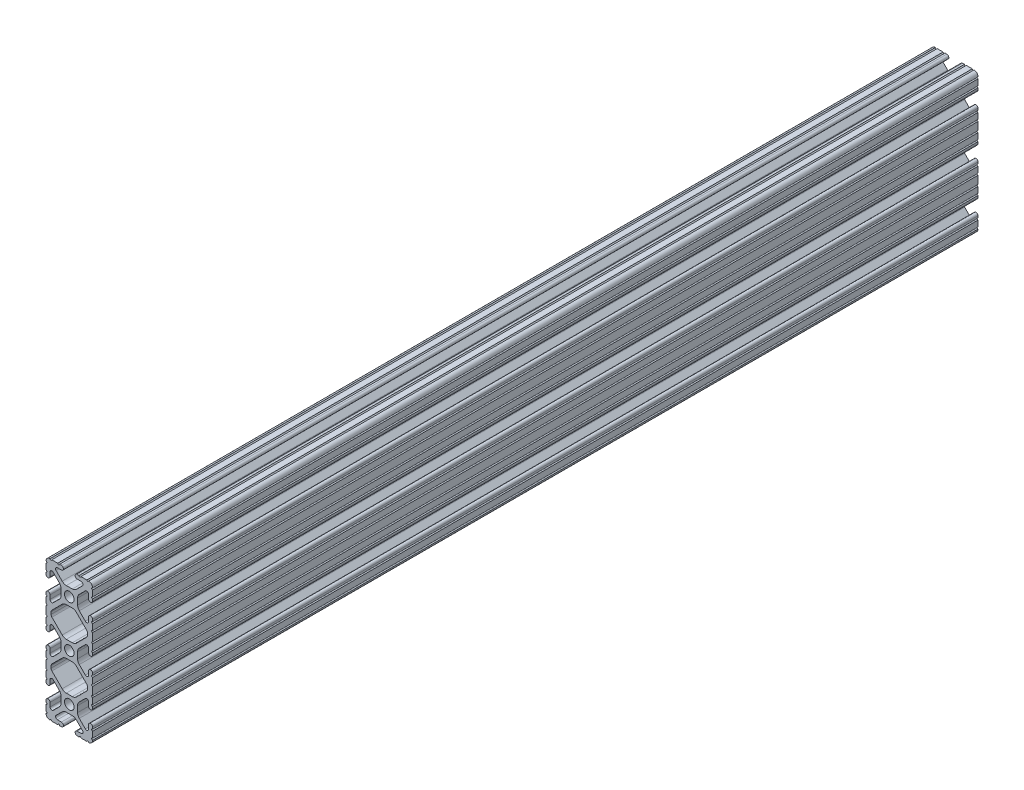
SolidWorks part; units mm, degrees
ref_plane "Front" through (0, 0, 0) normal (0, 0, 1) x (1, 0, 0)
ref_plane "Top" through (0, 0, 0) normal (0, 1, 0) x (1, 0, 0)
ref_plane "Right" through (0, 0, 0) normal (1, 0, 0) x (0, 0, -1)
sketch "Sketch1" plane through (0, 0, 0) normal (0, 0, 1) x (1, 0, 0)
  line L0 (-7.4908, -34.8742) -> (7.4908, -34.8742) construction
  line L1 (-3.1974, -36.9951) -> (3.1974, -36.9951) construction
  line L2 (-7.4908, 34.8742) -> (7.4908, 34.8742) construction
  line L3 (-3.1974, 36.9951) -> (3.1974, 36.9951) construction
  line L16 (-9.9314, -12.1463) -> (-9.9314, -13.2537)
  line L17 (-3.8759, -5.4384) -> (-9.4702, -11.0327)
  line L18 (1.6308, -4.5085) -> (-1.6308, -4.5085)
  line L19 (9.4702, -11.0327) -> (3.8759, -5.4384)
  line L20 (9.9314, -13.2537) -> (9.9314, -12.1463)
  line L21 (3.8759, -19.9616) -> (9.4702, -14.3673)
  line L22 (-1.6308, -20.8915) -> (1.6308, -20.8915)
  line L23 (-9.4702, -14.3673) -> (-3.8759, -19.9616)
  line L32 (-9.9314, 13.2537) -> (-9.9314, 12.1463)
  line L33 (-3.8759, 19.9616) -> (-9.4702, 14.3673)
  line L34 (1.6308, 20.8915) -> (-1.6308, 20.8915)
  line L35 (9.4702, 14.3673) -> (3.8759, 19.9616)
  line L36 (9.9314, 12.1463) -> (9.9314, 13.2537)
  line L37 (3.8759, 5.4384) -> (9.4702, 11.0327)
  line L38 (-1.6308, 4.5085) -> (1.6308, 4.5085)
  line L39 (-9.4702, 11.0327) -> (-3.8759, 5.4384)
  line L152 (-12.7, 34.9504) -> (-12.7, 31.7246)
  line L153 (-12.7, 30.7086) -> (-12.7, 29.7023)
  line L154 (-10.4902, 29.7023) -> (-10.4902, 31.8748)
  line L155 (-8.7558, 32.5932) -> (-5.4384, 29.2759)
  line L156 (-4.5085, 27.0308) -> (-4.5085, 23.7692)
  line L157 (-5.4384, 21.5241) -> (-8.7558, 18.2068)
  line L158 (-10.4902, 18.9252) -> (-10.4902, 21.0977)
  line L159 (-12.7, 21.0977) -> (-12.7, 20.0914)
  line L160 (-12.7, 19.0754) -> (-12.7, 15.8496)
  line L161 (-12.7, 14.8336) -> (-12.7, 10.5664)
  line L162 (-12.7, 9.5504) -> (-12.7, 6.3246)
  line L163 (-12.7, 5.3086) -> (-12.7, 4.3023)
  line L164 (-10.4902, 4.3023) -> (-10.4902, 6.4748)
  line L165 (-8.7558, 7.1932) -> (-5.4384, 3.8759)
  line L166 (-4.5085, 1.6308) -> (-4.5085, -1.6308)
  line L167 (-5.4384, -3.8759) -> (-8.7558, -7.1932)
  line L168 (-10.4902, -6.4748) -> (-10.4902, -4.3023)
  line L169 (-12.7, -4.3023) -> (-12.7, -5.3086)
  line L170 (-12.7, -6.3246) -> (-12.7, -9.5504)
  line L171 (-12.7, -10.5664) -> (-12.7, -14.8336)
  line L172 (-12.7, -15.8496) -> (-12.7, -19.0754)
  line L173 (-12.7, -20.0914) -> (-12.7, -21.0977)
  line L174 (-10.4902, -21.0977) -> (-10.4902, -18.9252)
  line L175 (-8.7558, -18.2068) -> (-5.4384, -21.5241)
  line L176 (-4.5085, -23.7692) -> (-4.5085, -27.0308)
  line L177 (-5.4384, -29.2759) -> (-8.7558, -32.5932)
  line L178 (-10.4902, -31.8748) -> (-10.4902, -29.7023)
  line L179 (-12.7, -29.7023) -> (-12.7, -30.7086)
  line L180 (-12.7, -31.7246) -> (-12.7, -34.9504)
  line L181 (-9.5504, -38.1) -> (-6.3246, -38.1)
  line L182 (-5.3086, -38.1) -> (-4.3023, -38.1)
  line L183 (-4.3023, -35.8902) -> (-6.4748, -35.8902)
  line L184 (-7.1932, -34.1558) -> (-3.8759, -30.8384)
  line L185 (-1.6308, -29.9085) -> (1.6308, -29.9085)
  line L186 (3.8759, -30.8384) -> (7.1932, -34.1558)
  line L187 (6.4748, -35.8902) -> (4.3023, -35.8902)
  line L188 (4.3023, -38.1) -> (5.3086, -38.1)
  line L189 (6.3246, -38.1) -> (9.5504, -38.1)
  line L190 (12.7, -34.9504) -> (12.7, -31.7246)
  line L191 (12.7, -30.7086) -> (12.7, -29.7023)
  line L192 (10.4902, -29.7023) -> (10.4902, -31.8748)
  line L193 (8.7558, -32.5932) -> (5.4384, -29.2759)
  line L194 (4.5085, -27.0308) -> (4.5085, -23.7692)
  line L195 (5.4384, -21.5241) -> (8.7558, -18.2068)
  line L196 (10.4902, -18.9252) -> (10.4902, -21.0977)
  line L197 (12.7, -21.0977) -> (12.7, -20.0914)
  line L198 (12.7, -19.0754) -> (12.7, -15.8496)
  line L199 (12.7, -14.8336) -> (12.7, -10.5664)
  line L200 (12.7, -9.5504) -> (12.7, -6.3246)
  line L201 (12.7, -5.3086) -> (12.7, -4.3023)
  line L202 (10.4902, -4.3023) -> (10.4902, -6.4748)
  line L203 (8.7558, -7.1932) -> (5.4384, -3.8759)
  line L204 (4.5085, -1.6308) -> (4.5085, 1.6308)
  line L205 (5.4384, 3.8759) -> (8.7558, 7.1932)
  line L206 (10.4902, 6.4748) -> (10.4902, 4.3023)
  line L207 (12.7, 4.3023) -> (12.7, 5.3086)
  line L208 (12.7, 6.3246) -> (12.7, 9.5504)
  line L209 (12.7, 10.5664) -> (12.7, 14.8336)
  line L210 (12.7, 15.8496) -> (12.7, 19.0754)
  line L211 (12.7, 20.0914) -> (12.7, 21.0977)
  line L212 (10.4902, 21.0977) -> (10.4902, 18.9252)
  line L213 (8.7558, 18.2068) -> (5.4384, 21.5241)
  line L214 (4.5085, 23.7692) -> (4.5085, 27.0308)
  line L215 (5.4384, 29.2759) -> (8.7558, 32.5932)
  line L216 (10.4902, 31.8748) -> (10.4902, 29.7023)
  line L217 (12.7, 29.7023) -> (12.7, 30.7086)
  line L218 (12.7, 31.7246) -> (12.7, 34.9504)
  line L219 (9.5504, 38.1) -> (6.3246, 38.1)
  line L220 (5.3086, 38.1) -> (4.3023, 38.1)
  line L221 (4.3023, 35.8902) -> (6.4748, 35.8902)
  line L222 (7.1932, 34.1558) -> (3.8759, 30.8384)
  line L223 (1.6308, 29.9085) -> (-1.6308, 29.9085)
  line L224 (-3.8759, 30.8384) -> (-7.1932, 34.1558)
  line L225 (-6.4748, 35.8902) -> (-4.3023, 35.8902)
  line L226 (-4.3023, 38.1) -> (-5.3086, 38.1)
  line L227 (-6.3246, 38.1) -> (-9.5504, 38.1)
  circle A2 centre (0, -25.4) radius 2.6035
  circle A4 centre (0, 0) radius 2.6035
  circle A6 centre (0, 25.4) radius 2.6035
  arc A18 (-9.9314, -13.2537) -> (-9.4702, -14.3673) centre (-8.3566, -13.2537) ccw
  arc A19 (-9.4702, -11.0327) -> (-9.9314, -12.1463) centre (-8.3566, -12.1463) ccw
  arc A20 (-1.6308, -4.5085) -> (-3.8759, -5.4384) centre (-1.6308, -7.6835) ccw
  arc A21 (3.8759, -5.4384) -> (1.6308, -4.5085) centre (1.6308, -7.6835) ccw
  arc A22 (9.9314, -12.1463) -> (9.4702, -11.0327) centre (8.3566, -12.1463) ccw
  arc A23 (9.4702, -14.3673) -> (9.9314, -13.2537) centre (8.3566, -13.2537) ccw
  arc A24 (1.6308, -20.8915) -> (3.8759, -19.9616) centre (1.6308, -17.7165) ccw
  arc A25 (-3.8759, -19.9616) -> (-1.6308, -20.8915) centre (-1.6308, -17.7165) ccw
  arc A36 (-9.9314, 12.1463) -> (-9.4702, 11.0327) centre (-8.3566, 12.1463) ccw
  arc A37 (-9.4702, 14.3673) -> (-9.9314, 13.2537) centre (-8.3566, 13.2537) ccw
  arc A38 (-1.6308, 20.8915) -> (-3.8759, 19.9616) centre (-1.6308, 17.7165) ccw
  arc A39 (3.8759, 19.9616) -> (1.6308, 20.8915) centre (1.6308, 17.7165) ccw
  arc A40 (9.9314, 13.2537) -> (9.4702, 14.3673) centre (8.3566, 13.2537) ccw
  arc A41 (9.4702, 11.0327) -> (9.9314, 12.1463) centre (8.3566, 12.1463) ccw
  arc A42 (1.6308, 4.5085) -> (3.8759, 5.4384) centre (1.6308, 7.6835) ccw
  arc A43 (-3.8759, 5.4384) -> (-1.6308, 4.5085) centre (-1.6308, 7.6835) ccw
  arc A168 (-10.5664, 38.1) -> (-12.7, 35.9664) centre (-10.592, 35.992) ccw
  arc A169 (-12.7, 34.9504) -> (-12.7, 35.9664) centre (-12.7, 35.4584) ccw
  arc A170 (-12.7, 30.7086) -> (-12.7, 31.7246) centre (-12.7, 31.2166) ccw
  arc A171 (-12.7, 29.7023) -> (-10.4902, 29.7023) centre (-11.5951, 29.7023) ccw
  arc A172 (-8.7558, 32.5932) -> (-10.4902, 31.8748) centre (-9.4742, 31.8748) ccw
  arc A173 (-4.5085, 27.0308) -> (-5.4384, 29.2759) centre (-7.6835, 27.0308) ccw
  arc A174 (-5.4384, 21.5241) -> (-4.5085, 23.7692) centre (-7.6835, 23.7692) ccw
  arc A175 (-10.4902, 18.9252) -> (-8.7558, 18.2068) centre (-9.4742, 18.9252) ccw
  arc A176 (-10.4902, 21.0977) -> (-12.7, 21.0977) centre (-11.5951, 21.0977) ccw
  arc A177 (-12.7, 19.0754) -> (-12.7, 20.0914) centre (-12.7, 19.5834) ccw
  arc A178 (-12.7, 14.8336) -> (-12.7, 15.8496) centre (-12.7, 15.3416) ccw
  arc A179 (-12.7, 9.5504) -> (-12.7, 10.5664) centre (-12.7, 10.0584) ccw
  arc A180 (-12.7, 5.3086) -> (-12.7, 6.3246) centre (-12.7, 5.8166) ccw
  arc A181 (-12.7, 4.3023) -> (-10.4902, 4.3023) centre (-11.5951, 4.3023) ccw
  arc A182 (-8.7558, 7.1932) -> (-10.4902, 6.4748) centre (-9.4742, 6.4748) ccw
  arc A183 (-4.5085, 1.6308) -> (-5.4384, 3.8759) centre (-7.6835, 1.6308) ccw
  arc A184 (-5.4384, -3.8759) -> (-4.5085, -1.6308) centre (-7.6835, -1.6308) ccw
  arc A185 (-10.4902, -6.4748) -> (-8.7558, -7.1932) centre (-9.4742, -6.4748) ccw
  arc A186 (-10.4902, -4.3023) -> (-12.7, -4.3023) centre (-11.5951, -4.3023) ccw
  arc A187 (-12.7, -6.3246) -> (-12.7, -5.3086) centre (-12.7, -5.8166) ccw
  arc A188 (-12.7, -10.5664) -> (-12.7, -9.5504) centre (-12.7, -10.0584) ccw
  arc A189 (-12.7, -15.8496) -> (-12.7, -14.8336) centre (-12.7, -15.3416) ccw
  arc A190 (-12.7, -20.0914) -> (-12.7, -19.0754) centre (-12.7, -19.5834) ccw
  arc A191 (-12.7, -21.0977) -> (-10.4902, -21.0977) centre (-11.5951, -21.0977) ccw
  arc A192 (-8.7558, -18.2068) -> (-10.4902, -18.9252) centre (-9.4742, -18.9252) ccw
  arc A193 (-4.5085, -23.7692) -> (-5.4384, -21.5241) centre (-7.6835, -23.7692) ccw
  arc A194 (-5.4384, -29.2759) -> (-4.5085, -27.0308) centre (-7.6835, -27.0308) ccw
  arc A195 (-10.4902, -31.8748) -> (-8.7558, -32.5932) centre (-9.4742, -31.8748) ccw
  arc A196 (-10.4902, -29.7023) -> (-12.7, -29.7023) centre (-11.5951, -29.7023) ccw
  arc A197 (-12.7, -31.7246) -> (-12.7, -30.7086) centre (-12.7, -31.2166) ccw
  arc A198 (-12.7, -35.9664) -> (-12.7, -34.9504) centre (-12.7, -35.4584) ccw
  arc A199 (-12.7, -35.9664) -> (-10.5664, -38.1) centre (-10.592, -35.992) ccw
  arc A200 (-9.5504, -38.1) -> (-10.5664, -38.1) centre (-10.0584, -38.1) ccw
  arc A201 (-5.3086, -38.1) -> (-6.3246, -38.1) centre (-5.8166, -38.1) ccw
  arc A202 (-4.3023, -38.1) -> (-4.3023, -35.8902) centre (-4.3023, -36.9951) ccw
  arc A203 (-7.1932, -34.1558) -> (-6.4748, -35.8902) centre (-6.4748, -34.8742) ccw
  arc A204 (-1.6308, -29.9085) -> (-3.8759, -30.8384) centre (-1.6308, -33.0835) ccw
  arc A205 (3.8759, -30.8384) -> (1.6308, -29.9085) centre (1.6308, -33.0835) ccw
  arc A206 (6.4748, -35.8902) -> (7.1932, -34.1558) centre (6.4748, -34.8742) ccw
  arc A207 (4.3023, -35.8902) -> (4.3023, -38.1) centre (4.3023, -36.9951) ccw
  arc A208 (6.3246, -38.1) -> (5.3086, -38.1) centre (5.8166, -38.1) ccw
  arc A209 (10.5664, -38.1) -> (9.5504, -38.1) centre (10.0584, -38.1) ccw
  arc A210 (10.5664, -38.1) -> (12.7, -35.9664) centre (10.592, -35.992) ccw
  arc A211 (12.7, -34.9504) -> (12.7, -35.9664) centre (12.7, -35.4584) ccw
  arc A212 (12.7, -30.7086) -> (12.7, -31.7246) centre (12.7, -31.2166) ccw
  arc A213 (12.7, -29.7023) -> (10.4902, -29.7023) centre (11.5951, -29.7023) ccw
  arc A214 (8.7558, -32.5932) -> (10.4902, -31.8748) centre (9.4742, -31.8748) ccw
  arc A215 (4.5085, -27.0308) -> (5.4384, -29.2759) centre (7.6835, -27.0308) ccw
  arc A216 (5.4384, -21.5241) -> (4.5085, -23.7692) centre (7.6835, -23.7692) ccw
  arc A217 (10.4902, -18.9252) -> (8.7558, -18.2068) centre (9.4742, -18.9252) ccw
  arc A218 (10.4902, -21.0977) -> (12.7, -21.0977) centre (11.5951, -21.0977) ccw
  arc A219 (12.7, -19.0754) -> (12.7, -20.0914) centre (12.7, -19.5834) ccw
  arc A220 (12.7, -14.8336) -> (12.7, -15.8496) centre (12.7, -15.3416) ccw
  arc A221 (12.7, -9.5504) -> (12.7, -10.5664) centre (12.7, -10.0584) ccw
  arc A222 (12.7, -5.3086) -> (12.7, -6.3246) centre (12.7, -5.8166) ccw
  arc A223 (12.7, -4.3023) -> (10.4902, -4.3023) centre (11.5951, -4.3023) ccw
  arc A224 (8.7558, -7.1932) -> (10.4902, -6.4748) centre (9.4742, -6.4748) ccw
  arc A225 (4.5085, -1.6308) -> (5.4384, -3.8759) centre (7.6835, -1.6308) ccw
  arc A226 (5.4384, 3.8759) -> (4.5085, 1.6308) centre (7.6835, 1.6308) ccw
  arc A227 (10.4902, 6.4748) -> (8.7558, 7.1932) centre (9.4742, 6.4748) ccw
  arc A228 (10.4902, 4.3023) -> (12.7, 4.3023) centre (11.5951, 4.3023) ccw
  arc A229 (12.7, 6.3246) -> (12.7, 5.3086) centre (12.7, 5.8166) ccw
  arc A230 (12.7, 10.5664) -> (12.7, 9.5504) centre (12.7, 10.0584) ccw
  arc A231 (12.7, 15.8496) -> (12.7, 14.8336) centre (12.7, 15.3416) ccw
  arc A232 (12.7, 20.0914) -> (12.7, 19.0754) centre (12.7, 19.5834) ccw
  arc A233 (12.7, 21.0977) -> (10.4902, 21.0977) centre (11.5951, 21.0977) ccw
  arc A234 (8.7558, 18.2068) -> (10.4902, 18.9252) centre (9.4742, 18.9252) ccw
  arc A235 (4.5085, 23.7692) -> (5.4384, 21.5241) centre (7.6835, 23.7692) ccw
  arc A236 (5.4384, 29.2759) -> (4.5085, 27.0308) centre (7.6835, 27.0308) ccw
  arc A237 (10.4902, 31.8748) -> (8.7558, 32.5932) centre (9.4742, 31.8748) ccw
  arc A238 (10.4902, 29.7023) -> (12.7, 29.7023) centre (11.5951, 29.7023) ccw
  arc A239 (12.7, 31.7246) -> (12.7, 30.7086) centre (12.7, 31.2166) ccw
  arc A240 (12.7, 35.9664) -> (12.7, 34.9504) centre (12.7, 35.4584) ccw
  arc A241 (12.7, 35.9664) -> (10.5664, 38.1) centre (10.592, 35.992) ccw
  arc A242 (9.5504, 38.1) -> (10.5664, 38.1) centre (10.0584, 38.1) ccw
  arc A243 (5.3086, 38.1) -> (6.3246, 38.1) centre (5.8166, 38.1) ccw
  arc A244 (4.3023, 38.1) -> (4.3023, 35.8902) centre (4.3023, 36.9951) ccw
  arc A245 (7.1932, 34.1558) -> (6.4748, 35.8902) centre (6.4748, 34.8742) ccw
  arc A246 (1.6308, 29.9085) -> (3.8759, 30.8384) centre (1.6308, 33.0835) ccw
  arc A247 (-3.8759, 30.8384) -> (-1.6308, 29.9085) centre (-1.6308, 33.0835) ccw
  arc A248 (-6.4748, 35.8902) -> (-7.1932, 34.1558) centre (-6.4748, 34.8742) ccw
  arc A249 (-4.3023, 35.8902) -> (-4.3023, 38.1) centre (-4.3023, 36.9951) ccw
  arc A250 (-6.3246, 38.1) -> (-5.3086, 38.1) centre (-5.8166, 38.1) ccw
  arc A251 (-10.5664, 38.1) -> (-9.5504, 38.1) centre (-10.0584, 38.1) ccw
extrude "Boss-Extrude1" add sketch "Sketch1" along normal mid plane 482.6
